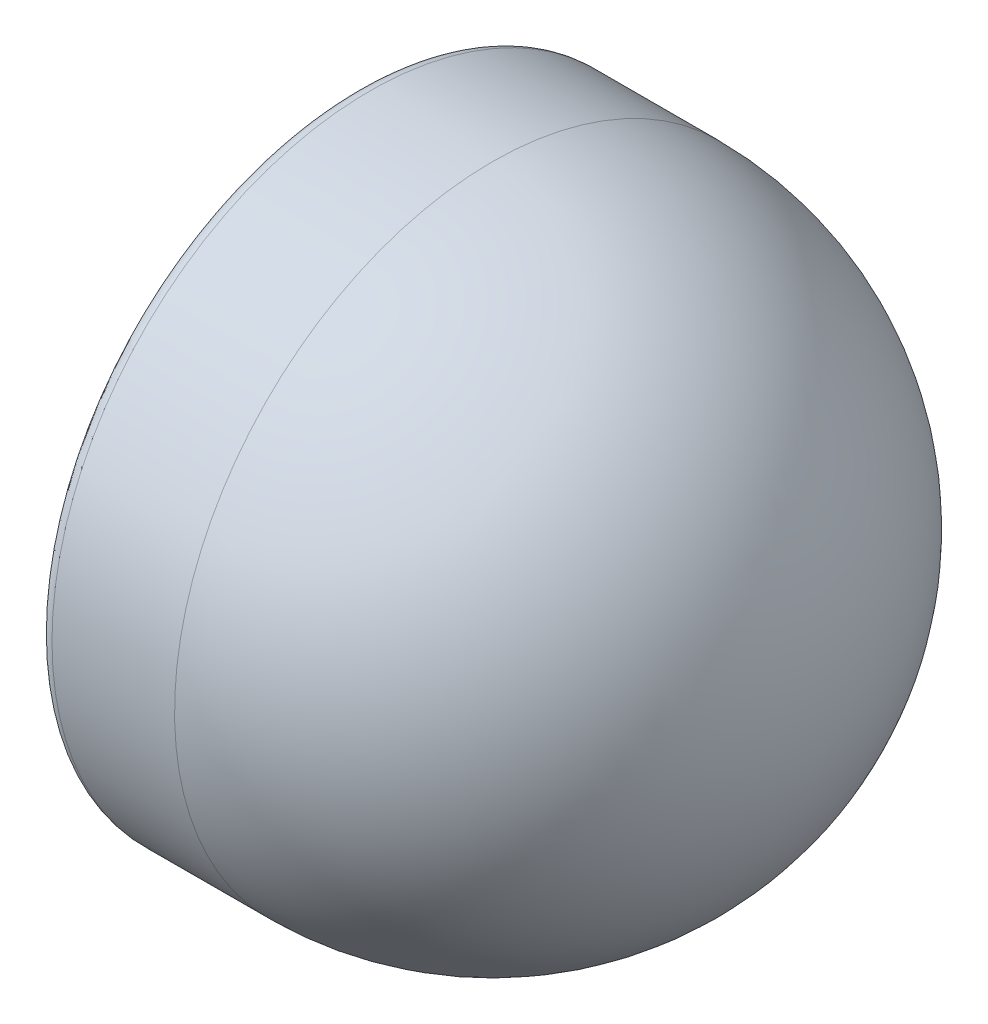
SolidWorks part; units mm, degrees
ref_plane "Front Plane" through (0, 0, 0) normal (0, 0, 1) x (1, 0, 0)
ref_plane "Top Plane" through (0, 0, 0) normal (0, 1, 0) x (1, 0, 0)
ref_plane "Right Plane" through (0, 0, 0) normal (1, 0, 0) x (0, 0, -1)
sketch "Sketch1" plane through (0, 0, 0) normal (0, 0, 1) x (1, 0, 0)
  line L0 (0, 0) -> (-128.4438, 0) construction
  line L1 (-70, 70) -> (-97, 70)
  line L14 (-100, 67) -> (-100, 61.5)
  line L15 (-98.5, 60) -> (-96.6213, 60)
  line L16 (-95.5607, 60.4393) -> (-92, 64)
  line L17 (-70, 69) -> (-97, 69)
  line L18 (-99, 67) -> (-99, 61.5)
  line L19 (-98.5, 61) -> (-96.6213, 61)
  line L20 (-96.2678, 61.1464) -> (-92.7071, 64.7071)
  line L21 (-92.7071, 64.7071) -> (-92, 64.7071)
  line L22 (-92, 64.7071) -> (-92, 64)
  line L23 (-1, 0) -> (0, 0)
  arc A8 (0, 0) -> (-70, 70) centre (-70, 0) ccw
  arc A9 (-97, 70) -> (-100, 67) centre (-97, 67) ccw
  arc A10 (-95.5607, 60.4393) -> (-96.6213, 60) centre (-96.6213, 61.5) cw
  arc A11 (-100, 61.5) -> (-98.5, 60) centre (-98.5, 61.5) ccw
  arc A12 (-1, 0) -> (-70, 69) centre (-70, 0) ccw
  arc A13 (-97, 69) -> (-99, 67) centre (-97, 67) ccw
  arc A14 (-99, 61.5) -> (-98.5, 61) centre (-98.5, 61.5) ccw
  arc A15 (-96.2678, 61.1464) -> (-96.6213, 61) centre (-96.6213, 61.5) cw
  point P13 (-100, 70)
  point P16 (-96, 60)
  point P19 (-100, 60)
  dimension "D1" = 70
  dimension "D2" = 30
  dimension "D6" = 3
  dimension "D7" = 1.5
  dimension "D3" = 10
  dimension "D4" = 4
  dimension "D5" = 135
  dimension "D9" = 7
  dimension "D8" = 1
revolve "Revolve6" add sketch "Sketch1" angle 360 about L0
